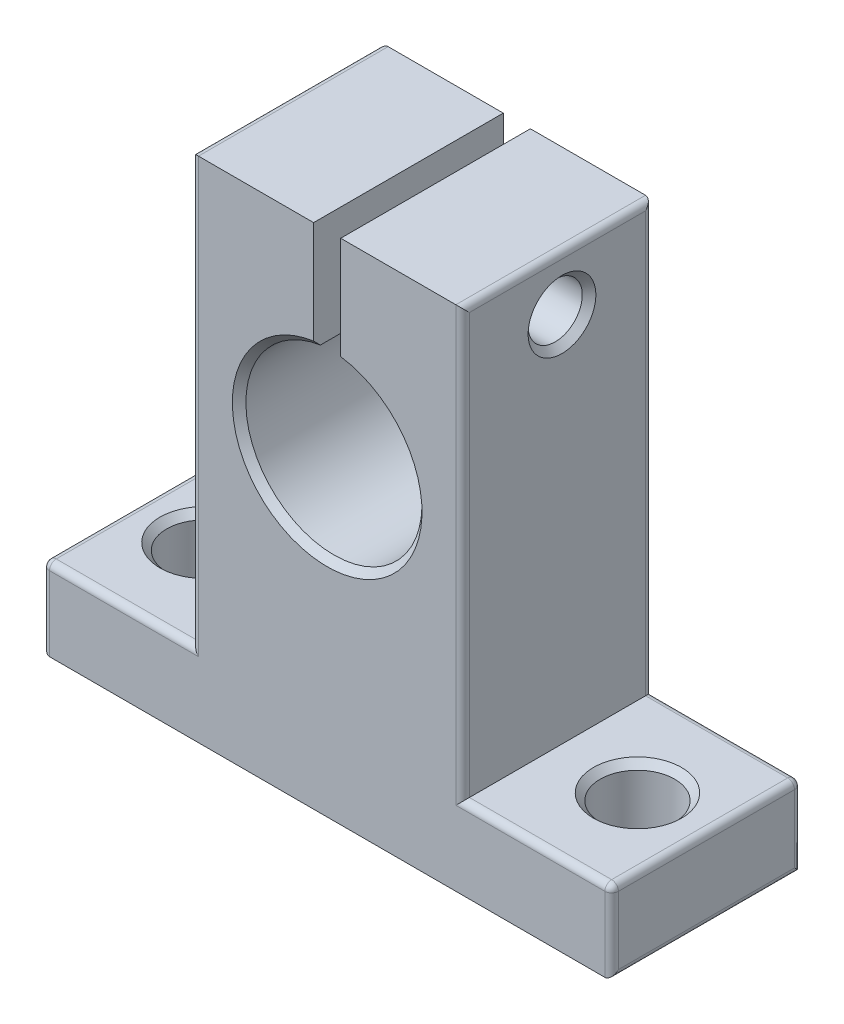
SolidWorks part; units mm, degrees
material "1060 Alloy"
ref_plane "Front Plane" through (0, 0, 0) normal (0, 0, 1) x (1, 0, 0)
ref_plane "Top Plane" through (0, 0, 0) normal (0, 1, 0) x (1, 0, 0)
ref_plane "Right Plane" through (0, 0, 0) normal (1, 0, 0) x (0, 0, -1)
sketch "Sketch1" plane through (0, 0, 0) normal (0, 0, 1) x (1, 0, 0)
  line L0 (0, 0) -> (-50000, 0) construction
  line L1 (0, 0) -> (0, 50000) construction
  line L2 (-21, -3) -> (-21, 3)
  line L3 (-21, 3) -> (-10, 3)
  line L4 (-10, 3) -> (-10, 34.5)
  line L5 (-10, 34.5) -> (-1, 34.5)
  line L6 (10, 34.5) -> (10, 3)
  line L7 (10, 3) -> (21, 3)
  line L8 (21, 3) -> (21, -3)
  line L9 (21, -3) -> (-21, -3)
  line L10 (16, -3) -> (16, 3) construction
  line L11 (-16, -3) -> (-16, 3) construction
  line L12 (-1, 34.5) -> (-1, 26.4226)
  line L13 (1, 34.5) -> (1, 26.4226)
  line L14 (1, 34.5) -> (10, 34.5)
  arc A0 (-1, 26.4226) -> (1, 26.4226) centre (0, 20) ccw
  point P8 (-21, 0)
  point P15 (0, -3)
  point P21 (16, 0)
  dimension "Shaft Diameter" = 13
  dimension "W" = 42
  dimension "P" = 20
  dimension "F" = 37.5
  dimension "G" = 6
  dimension "B" = 32
  dimension "D1" = 2
  dimension "h" = 23
extrude "Boss-Extrude1" add sketch "Sketch1" along normal mid plane 14
sketch "Sketch2" plane through (0, 3, 0) normal (0, 1, 0) x (1, 0, 0)
  line L0 (0, 0) -> (50000, 0) construction
  line L1 (0.3141, 0) -> (-49999.6859, 0) construction
  line L2 (-0.0955, 2.4842) -> (-0.0955, 50002.4842) construction
  circle A0 centre (15.9045, 0) radius 2.75
  circle A1 centre (-16.0955, 0) radius 2.75
  dimension "B" = 32
  dimension "S" = 5.5
extrude "Cut-Extrude1" cut sketch "Sketch2" against normal through all
sketch "Sketch5" plane through (-1, 0, 0) normal (1, 0, 0) x (0, 0, -1)
  line L0 (-7, 30.4613) -> (7, 30.4613) construction
  line L1 (7, 26.4226) -> (7, 34.5) construction
  line L2 (0, 34.5) -> (0, 26.4226) construction
  line L3 (-7, 34.5) -> (7, 34.5) construction
  line L4 (-7, 26.4226) -> (7, 26.4226) construction
  line L5 (-7, 26.4226) -> (-7, 34.5) construction
  circle A0 centre (0.3307, 30.4613) radius 2
  dimension "Clamping bold" = 4
extrude "Cut-Extrude2" cut sketch "Sketch5" against normal through all both and the other way through all
chamfer "Chamfer2" distance 0.5 angle 45 6 edges at (0, 13.5, -7) (0, 13.5, 7) (-10, 30.4613, -2.3307) (-13.3455, 3, 0) (10, 30.4613, 1.6693) (13.1545, 3, 0)
fillet "Fillet2" radius 0.5 18 edges at (21, -3, 0) (21, 0, 7) (21, 3, 0) (21, 0, -7) (-21, 3, 0) (-21, 0, 7) (-21, -3, 0) (-21, 0, -7) (-15.5, 3, -7) (-15.5, 3, 7) (-10, 18.75, 7) (-10, 34.5, 0) (-10, 18.75, -7) (10, 18.75, -7) (10, 18.75, 7) (15.5, 3, 7) (15.5, 3, -7) (10, 34.5, 0)
equation "\"W\"= \"W@Sketch1\"'Width"
equation "\"B\"= \"B@Sketch1\"'between hold"
equation "\"F\"= \"F@Sketch1\"'Hight"
equation "\"P\"= \"P@Sketch1\""
equation "\"G\"= \"G@Sketch1\""
equation "\"Shaft diameter\"= \"Shaft Diameter@Sketch1\""
equation "\"S\"= 5.5'M5"
equation "\"Clamping bold\"= 4'M4"
equation "\"h\"= \"h@Sketch1\""
